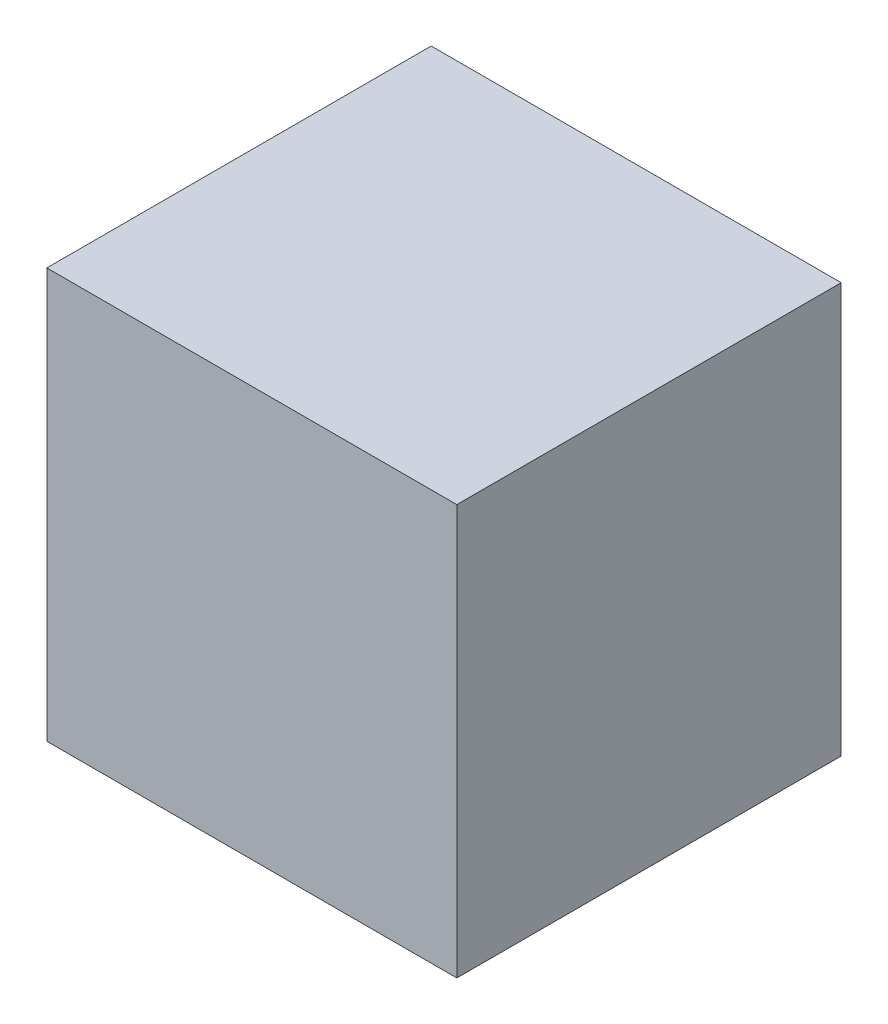
SolidWorks part; units mm, degrees
material "Rubber"
ref_plane "Front Plane" through (0, 0, 0) normal (0, 0, 1) x (1, 0, 0)
ref_plane "Top Plane" through (0, 0, 0) normal (0, 1, 0) x (1, 0, 0)
ref_plane "Right Plane" through (0, 0, 0) normal (1, 0, 0) x (0, 0, -1)
sketch "Sketch1" plane through (0, 0, 0) normal (0, 1, 0) x (1, 0, 0)
  line L1 (0, 0) -> (16, 0)
  line L2 (0, 0) -> (0, -15)
  line L3 (0, -15) -> (16, -15)
  line L4 (16, 0) -> (16, -15)
  dimension "D1" = 15
  dimension "D2" = 16
extrude "Boss-Extrude1" add sketch "Sketch1" along normal blind 16
